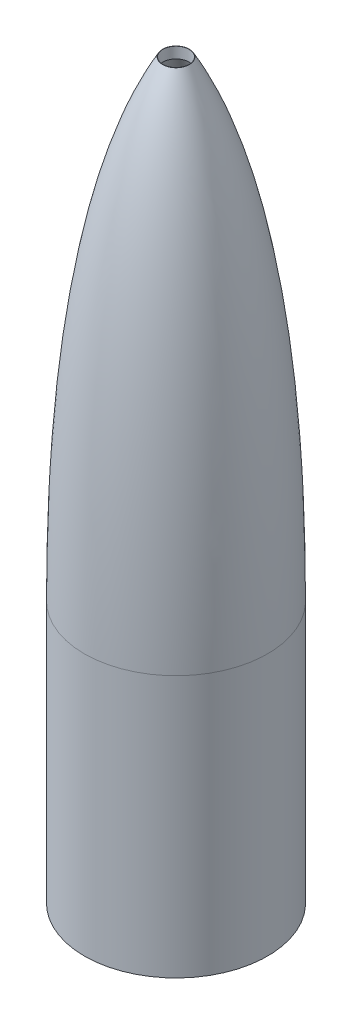
SolidWorks part; units mm, degrees
ref_plane "Piano frontale" through (0, 0, 0) normal (0, 0, 1) x (1, 0, 0)
ref_plane "Piano superiore" through (0, 0, 0) normal (0, 1, 0) x (1, 0, 0)
ref_plane "Piano destro" through (0, 0, 0) normal (1, 0, 0) x (0, 0, -1)
sketch "Schizzo1" plane through (0, 0, 0) normal (0, 1, 0) x (1, 0, 0)
  line L0 (0, -54.0204) -> (0, 55.7677) construction
  line L1 (-109.7881, 0) -> (99.3044, 0) construction
  circle A0 centre (0, 0) radius 17.5
extrude "Estrusione-Estrusione1" add sketch "Schizzo1" along normal blind 50
ref_plane "Piano1" through (0, 140, 0) normal (0, 1, 0) x (1, 0, 0)
sketch "Schizzo7" plane through (0, 0, 0) normal (0, 0, 1) x (1, 0, 0)
  line L3 (19.25, 140) -> (-19.25, 140) construction
  line L4 (0, 140) -> (-2.55, 140)
  line L5 (-17.5, 50) -> (-17.5, 144.4382) construction
  line L6 (-2.55, 140) -> (-17.5, 113.6279) construction
  line L7 (-17.5, 113.6279) -> (-17.5, 50) construction
  line L8 (-28.9012, 113.6279) -> (8.7353, 113.6279) construction
  line L9 (0, 138.8) -> (-2, 138.8)
  line L10 (-2, 138.8) -> (-16.3, 113.6279) construction
  line L11 (-16.3, 113.6279) -> (-16.3, 50) construction
  line L12 (-17.5, 50) -> (-16.3, 50)
  line L13 (0, 138.8) -> (0, 140)
  line L14 (0, 50) -> (0, 140) construction
  line L15 (17.5, 50) -> (-17.5, 50) construction
  spline S0 degree 2 poles (-2.55, 140) (-17.5, 113.6279) (-17.5, 50) knots 0 0 0 1 1 1
  spline S1 degree 2 poles (-2, 138.8) (-16.3, 113.6279) (-16.3, 50) knots 0 0 0 1 1 1
  dimension "D2" = 1.2
  dimension "D1" = 2
  dimension "D3" = 1.2
  dimension "D4" = 2.55
revolve "Rivoluzione1" add sketch "Schizzo7" angle 360 about L14
sketch "Schizzo10" plane through (0, 0, 0) normal (0, 1, 0) x (1, 0, 0)
  circle A0 centre (0, 0) radius 16.3
extrude "Taglio-Estrusione1" cut sketch "Schizzo10" along normal up to next
sketch "Schizzo14" plane through (0, 140, 0) normal (0, 1, 0) x (1, 0, 0)
  circle A0 centre (0, 0) radius 2.5
extrude "Taglio-Estrusione3" cut sketch "Schizzo14" against normal through all and the other way through all
sketch "Sketch1" plane through (0, 0, 0) normal (0, -1, 0) x (1, 0, 0)
  circle A0 centre (0, 0) radius 14.8
  circle M2 centre (0, 0) radius 16.3
extrude "Boss-Extrude3" add sketch "Sketch1" against normal blind 15 contours A0 M2
sketch "Sketch2" plane through (0, 0, 0) normal (0, -1, 0) x (1, 0, 0)
  line L0 (-14.8, 0) -> (14.8, 0)
  line L1 (-14.8, -3.6) -> (-14.8, 3.6)
  line L2 (-14.8, 3.6) -> (-10.8451, 3.6)
  line L3 (-14.8, -3.6) -> (-10.8451, -3.6)
  line L4 (0, 0) -> (0, 10.7136) construction
  line L5 (14.8, -3.6) -> (10.8451, -3.6)
  line L6 (14.8, 3.6) -> (10.8451, 3.6)
  line L7 (14.8, -3.6) -> (14.8, 3.6)
  circle A0 centre (0, 0) radius 14.8 construction
  arc A1 (-10.8451, 3.6) -> (-10.8451, -3.6) centre (-10.8451, 0) cw
  circle A2 centre (-10.8451, 0) radius 2.2
  circle A3 centre (10.8451, 0) radius 2.2
  arc A4 (10.8451, 3.6) -> (10.8451, -3.6) centre (10.8451, 0) ccw
  point P8 (-14.8, 0)
  circle M5 centre (0, 0) radius 14.8
extrude "Boss-Extrude4" add sketch "Sketch2" against normal blind 5 contours A2 L0 L3 A1 M5 | A2 L0 A1 L2 M5 | L6 A4 L0 A3 M5 | L0 A4 L5 A3 M5
